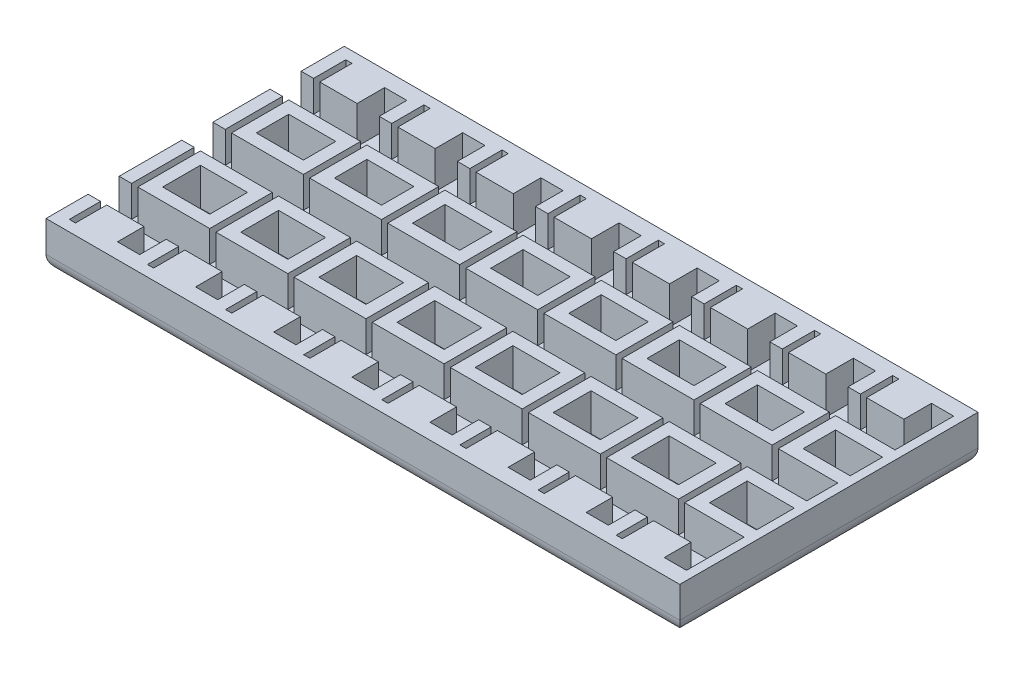
SolidWorks part; units mm, degrees
ref_plane "Alzado" through (0, 0, 0) normal (0, 0, 1) x (1, 0, 0)
ref_plane "Planta" through (0, 0, 0) normal (0, 1, 0) x (1, 0, 0)
ref_plane "Vista lateral" through (0, 0, 0) normal (1, 0, 0) x (0, 0, -1)
sketch "Sketch1" plane through (0, 0, 0) normal (0, 1, 0) x (1, 0, 0)
  line L1 (-102, -48) -> (102, -48)
  line L2 (-102, -48) -> (-102, 48)
  line L3 (-102, 48) -> (102, 48)
  line L4 (102, -48) -> (102, 48)
  line L5 (-102, -48) -> (102, 48) construction
  line L6 (-102, 48) -> (102, -48) construction
  point P0 (0, 0)
  dimension "D1" = 96
  dimension "D2" = 204
extrude "Boss-Extrude1" add sketch "Sketch1" along normal blind 15
sketch "Sketch2" plane through (0, 15, 0) normal (0, 1, 0) x (1, 0, 0)
  line L0 (-102, 48) -> (-102, -48) construction
  line L1 (-98, 44.5) -> (-96, 44.5)
  line L2 (-98, 44.5) -> (-98, -44.5)
  line L3 (-98, -44.5) -> (-96, -44.5)
  line L4 (-96, 44.5) -> (-96, -44.5)
  line L5 (-98, 44.5) -> (-96, -44.5) construction
  line L6 (-98, -44.5) -> (-96, 44.5) construction
  line L7 (-72.854, 44.5) -> (-72.854, -44.5)
  line L8 (-72.854, 44.5) -> (-70.854, 44.5)
  line L9 (-70.854, 44.5) -> (-70.854, -44.5)
  line L10 (-72.854, -44.5) -> (-70.854, -44.5)
  line L11 (-47.708, 44.5) -> (-47.708, -44.5)
  line L12 (-47.708, 44.5) -> (-45.708, 44.5)
  line L13 (-45.708, 44.5) -> (-45.708, -44.5)
  line L14 (-47.708, -44.5) -> (-45.708, -44.5)
  line L15 (-22.562, 44.5) -> (-22.562, -44.5)
  line L16 (-22.562, 44.5) -> (-20.562, 44.5)
  line L17 (-20.562, 44.5) -> (-20.562, -44.5)
  line L18 (-22.562, -44.5) -> (-20.562, -44.5)
  line L19 (2.584, 44.5) -> (2.584, -44.5)
  line L20 (2.584, 44.5) -> (4.584, 44.5)
  line L21 (4.584, 44.5) -> (4.584, -44.5)
  line L22 (2.584, -44.5) -> (4.584, -44.5)
  line L23 (27.73, 44.5) -> (27.73, -44.5)
  line L24 (27.73, 44.5) -> (29.73, 44.5)
  line L25 (29.73, 44.5) -> (29.73, -44.5)
  line L26 (27.73, -44.5) -> (29.73, -44.5)
  line L27 (52.876, 44.5) -> (52.876, -44.5)
  line L28 (52.876, 44.5) -> (54.876, 44.5)
  line L29 (54.876, 44.5) -> (54.876, -44.5)
  line L30 (52.876, -44.5) -> (54.876, -44.5)
  line L31 (78.022, 44.5) -> (78.022, -44.5)
  line L32 (78.022, 44.5) -> (80.022, 44.5)
  line L33 (80.022, 44.5) -> (80.022, -44.5)
  line L34 (78.022, -44.5) -> (80.022, -44.5)
  line L35 (-72.854, 0) -> (-70.854, 0)
  point P4 (-97, 0)
  point P39 (-71.854, 0)
  dimension "D1" = 2
  dimension "D2" = 89
  dimension "D3" = 4
  dimension "D5" = 25.146
  dimension "D4" = 8
extrude "Cut-Extrude1" cut sketch "Sketch2" against normal blind 10 contours L2 L3 L4 L1 | L9 L10 L7 L8 | L11 L14 L13 L12 | L15 L18 L17 L16 | L19 L22 L21 L20 | L23 L26 L25 L24 | L29 L30 L27 L28 | L31 L34 L33 L32
sketch "Sketch3" plane through (0, 15, 0) normal (0, 1, 0) x (1, 0, 0)
  line L0 (-96, 5.7) -> (-88, 5.7)
  line L1 (-96, 44.5) -> (-96, -44.5) construction
  line L2 (-88, 5.7) -> (-88, -4.3)
  line L3 (-88, -4.3) -> (-96, -4.3)
  line L4 (-96, -4.3) -> (-96, 5.7)
  line L5 (-96, 34.125) -> (-88, 34.125)
  line L6 (-88, 34.125) -> (-88, 24.125)
  line L7 (-88, 24.125) -> (-96, 24.125)
  line L8 (-96, 24.125) -> (-96, 34.125)
  line L9 (-96, -24.45) -> (-88, -24.45)
  line L10 (-88, -24.45) -> (-88, -34.45)
  line L11 (-88, -34.45) -> (-96, -34.45)
  line L12 (-96, -34.45) -> (-96, -24.45)
  line L13 (-96, 0.7) -> (-88, 0.7) construction
  line L14 (-88, 29.125) -> (-96, 29.125) construction
  line L15 (-88, -29.45) -> (-96, -29.45) construction
  line L16 (-98, 44.5) -> (-98, -44.5) construction
  line L17 (-96, -43.875) -> (-98, -43.875) construction
  line L18 (-96, -43.875) -> (-96, 43.875) construction
  line L19 (-96, 43.875) -> (-98, 43.875) construction
  line L20 (-98, -43.875) -> (-98, 43.875) construction
  line L21 (-96, -43.875) -> (-98, 43.875) construction
  line L22 (-96, 43.875) -> (-98, -43.875) construction
  line L23 (-70.854, 24.125) -> (-70.854, 34.125)
  line L24 (-70.854, 34.125) -> (-62.854, 34.125)
  line L25 (-62.854, 34.125) -> (-62.854, 24.125)
  line L26 (-62.854, 24.125) -> (-70.854, 24.125)
  line L27 (-70.854, -4.3) -> (-70.854, 5.7)
  line L28 (-70.854, 5.7) -> (-62.854, 5.7)
  line L29 (-62.854, 5.7) -> (-62.854, -4.3)
  line L30 (-62.854, -4.3) -> (-70.854, -4.3)
  line L31 (-70.854, -34.45) -> (-70.854, -24.45)
  line L32 (-70.854, -24.45) -> (-62.854, -24.45)
  line L33 (-62.854, -24.45) -> (-62.854, -34.45)
  line L34 (-62.854, -34.45) -> (-70.854, -34.45)
  line L35 (-45.708, 24.125) -> (-45.708, 34.125)
  line L36 (-45.708, 34.125) -> (-37.708, 34.125)
  line L37 (-37.708, 34.125) -> (-37.708, 24.125)
  line L38 (-37.708, 24.125) -> (-45.708, 24.125)
  line L39 (-45.708, -4.3) -> (-45.708, 5.7)
  line L40 (-45.708, 5.7) -> (-37.708, 5.7)
  line L41 (-37.708, 5.7) -> (-37.708, -4.3)
  line L42 (-37.708, -4.3) -> (-45.708, -4.3)
  line L43 (-45.708, -34.45) -> (-45.708, -24.45)
  line L44 (-45.708, -24.45) -> (-37.708, -24.45)
  line L45 (-37.708, -24.45) -> (-37.708, -34.45)
  line L46 (-37.708, -34.45) -> (-45.708, -34.45)
  line L47 (-20.562, 24.125) -> (-20.562, 34.125)
  line L48 (-20.562, 34.125) -> (-12.562, 34.125)
  line L49 (-12.562, 34.125) -> (-12.562, 24.125)
  line L50 (-12.562, 24.125) -> (-20.562, 24.125)
  line L51 (-20.562, -4.3) -> (-20.562, 5.7)
  line L52 (-20.562, 5.7) -> (-12.562, 5.7)
  line L53 (-12.562, 5.7) -> (-12.562, -4.3)
  line L54 (-12.562, -4.3) -> (-20.562, -4.3)
  line L55 (-20.562, -34.45) -> (-20.562, -24.45)
  line L56 (-20.562, -24.45) -> (-12.562, -24.45)
  line L57 (-12.562, -24.45) -> (-12.562, -34.45)
  line L58 (-12.562, -34.45) -> (-20.562, -34.45)
  line L59 (4.584, 24.125) -> (4.584, 34.125)
  line L60 (4.584, 34.125) -> (12.584, 34.125)
  line L61 (12.584, 34.125) -> (12.584, 24.125)
  line L62 (12.584, 24.125) -> (4.584, 24.125)
  line L63 (4.584, -4.3) -> (4.584, 5.7)
  line L64 (4.584, 5.7) -> (12.584, 5.7)
  line L65 (12.584, 5.7) -> (12.584, -4.3)
  line L66 (12.584, -4.3) -> (4.584, -4.3)
  line L67 (4.584, -34.45) -> (4.584, -24.45)
  line L68 (4.584, -24.45) -> (12.584, -24.45)
  line L69 (12.584, -24.45) -> (12.584, -34.45)
  line L70 (12.584, -34.45) -> (4.584, -34.45)
  line L71 (29.73, 24.125) -> (29.73, 34.125)
  line L72 (29.73, 34.125) -> (37.73, 34.125)
  line L73 (37.73, 34.125) -> (37.73, 24.125)
  line L74 (37.73, 24.125) -> (29.73, 24.125)
  line L75 (29.73, -4.3) -> (29.73, 5.7)
  line L76 (29.73, 5.7) -> (37.73, 5.7)
  line L77 (37.73, 5.7) -> (37.73, -4.3)
  line L78 (37.73, -4.3) -> (29.73, -4.3)
  line L79 (29.73, -34.45) -> (29.73, -24.45)
  line L80 (29.73, -24.45) -> (37.73, -24.45)
  line L81 (37.73, -24.45) -> (37.73, -34.45)
  line L82 (37.73, -34.45) -> (29.73, -34.45)
  line L83 (54.876, 24.125) -> (54.876, 34.125)
  line L84 (54.876, 34.125) -> (62.876, 34.125)
  line L85 (62.876, 34.125) -> (62.876, 24.125)
  line L86 (62.876, 24.125) -> (54.876, 24.125)
  line L87 (54.876, -4.3) -> (54.876, 5.7)
  line L88 (54.876, 5.7) -> (62.876, 5.7)
  line L89 (62.876, 5.7) -> (62.876, -4.3)
  line L90 (62.876, -4.3) -> (54.876, -4.3)
  line L91 (54.876, -34.45) -> (54.876, -24.45)
  line L92 (54.876, -24.45) -> (62.876, -24.45)
  line L93 (62.876, -24.45) -> (62.876, -34.45)
  line L94 (62.876, -34.45) -> (54.876, -34.45)
  line L95 (80.022, 24.125) -> (80.022, 34.125)
  line L96 (80.022, 34.125) -> (88.022, 34.125)
  line L97 (88.022, 34.125) -> (88.022, 24.125)
  line L98 (88.022, 24.125) -> (80.022, 24.125)
  line L99 (80.022, -4.3) -> (80.022, 5.7)
  line L100 (80.022, 5.7) -> (88.022, 5.7)
  line L101 (88.022, 5.7) -> (88.022, -4.3)
  line L102 (88.022, -4.3) -> (80.022, -4.3)
  line L103 (80.022, -34.45) -> (80.022, -24.45)
  line L104 (80.022, -24.45) -> (88.022, -24.45)
  line L105 (88.022, -24.45) -> (88.022, -34.45)
  line L106 (88.022, -34.45) -> (80.022, -34.45)
  line L107 (-70.854, 44.5) -> (-70.854, -44.5) construction
  point P22 (-97, 0)
  dimension "D1" = 10
  dimension "D2" = 8
  dimension "D3" = 87.75
  dimension "D4" = 14.75
  dimension "D5" = 28.425
  dimension "D6" = 30.15
  dimension "D7" = 8
extrude "Cut-Extrude2" cut sketch "Sketch3" against normal blind 12
fillet "Fillet1" radius 5 4 edges at (0, 0, -48) (-102, 0, 0) (0, 0, 48) (102, 0, 0)
sketch "Sketch5" plane through (0, 15, 0) normal (0, 1, 0) x (1, 0, 0)
  line L1 (-76.854, 20.125) -> (-92, 20.125)
  line L2 (-76.854, 20.125) -> (-76.854, 9.7)
  line L3 (-76.854, 9.7) -> (-92, 9.7)
  line L4 (-92, 20.125) -> (-92, 9.7)
  line L5 (-76.854, 20.125) -> (-92, 9.7) construction
  line L6 (-76.854, 9.7) -> (-92, 20.125) construction
  line L7 (-76.854, -8.3) -> (-92, -8.3)
  line L8 (-76.854, -8.3) -> (-76.854, -20.45)
  line L9 (-76.854, -20.45) -> (-92, -20.45)
  line L10 (-92, -8.3) -> (-92, -20.45)
  line L11 (-76.854, -8.3) -> (-92, -20.45) construction
  line L12 (-76.854, -20.45) -> (-92, -8.3) construction
  line L13 (-72.854, 44.5) -> (-72.854, -44.5) construction
  line L14 (-96, -4.3) -> (-96, -24.45) construction
  line L15 (-88, -24.45) -> (-96, -24.45) construction
  line L16 (-96, -4.3) -> (-88, -4.3) construction
  line L17 (-88, 5.7) -> (-96, 5.7) construction
  line L18 (-96, 24.125) -> (-96, 5.7) construction
  line L19 (-96, 24.125) -> (-88, 24.125) construction
  line L20 (-72.854, 44.5) -> (-72.854, -44.5) construction
  line L21 (-88, -4.3) -> (-88, 5.7) construction
  line L22 (-84, -4.3) -> (-76.854, -4.3)
  line L23 (-84, -4.3) -> (-84, 5.7)
  line L24 (-84, 5.7) -> (-76.854, 5.7)
  line L25 (-76.854, -4.3) -> (-76.854, 5.7)
  line L26 (-84, -4.3) -> (-76.854, 5.7) construction
  line L27 (-84, 5.7) -> (-76.854, -4.3) construction
  line L31 (-84, -4.3) -> (-84, 5.7) construction
  line L32 (-84, -4.3) -> (-76.854, -4.3) construction
  line L33 (-76.854, -4.3) -> (-76.854, 5.7) construction
  line L34 (-84, 5.7) -> (-76.854, 5.7) construction
  line L39 (-102, -48) -> (102, -48) construction
  line L40 (-84, 43) -> (-76.854, 43)
  line L41 (-84, 43) -> (-84, 24.125)
  line L42 (-84, 24.125) -> (-76.854, 24.125)
  line L43 (-76.854, 43) -> (-76.854, 24.125)
  line L44 (-84, 43) -> (-76.854, 24.125) construction
  line L45 (-84, 24.125) -> (-76.854, 43) construction
  line L46 (-84, -24.45) -> (-76.854, -24.45)
  line L47 (-84, -24.45) -> (-84, -43)
  line L48 (-84, -43) -> (-76.854, -43)
  line L49 (-76.854, -24.45) -> (-76.854, -43)
  line L50 (-84, -24.45) -> (-76.854, -43) construction
  line L51 (-84, -43) -> (-76.854, -24.45) construction
  line L52 (102, 48) -> (-102, 48) construction
  line L53 (-84, -111.973) -> (-84, -101.973) [skipped]
  line L54 (-84, -111.973) -> (-76.854, -111.973) [skipped]
  line L55 (-76.854, -111.973) -> (-76.854, -101.973) [skipped]
  line L56 (-84, -101.973) -> (-76.854, -101.973) [skipped]
  line L57 (-84, 103.373) -> (-84, 113.373) [skipped]
  line L58 (-76.854, 103.373) -> (-76.854, 113.373) [skipped]
  line L59 (-84, 113.373) -> (-76.854, 113.373) [skipped]
  line L60 (-84, 103.373) -> (-76.854, 103.373) [skipped]
  point P0 (-84.427, 14.9125)
  point P5 (-84.427, -14.375)
  point P28 (-80.427, 0.7)
  point P34 (-80.427, 33.5625)
  point P50 (-80.427, -33.725)
  point P57 (-80.427, -43)
  dimension "D1" = 4
  dimension "D2" = 4
  dimension "D3" = 4
  dimension "D4" = 4
  dimension "D5" = 4
  dimension "D6" = 4
  dimension "D7" = 4
  dimension "D8" = 4
  dimension "D9" = 4
  dimension "D10" = 4
  dimension "D11" = 4
  dimension "D12" = 4
  dimension "D15" = 5
  dimension "D16" = 5
  dimension "D17" = 4
  dimension "D13" = 2
  dimension "D14" = 2
extrude "Cut-Extrude3" cut sketch "Sketch5" against normal blind 12
pattern_linear "LPattern1" count 8 spacing 25.146 along (1, 0, 0) of "Cut-Extrude3"
hole_wizard "CSK for M4 Hex Socket Countersunk Cap Screw1" positions "Sketch7" profile "Sketch8" countersink size "M4" standard "ISO" end condition through all
sketch "Sketch7" plane through (0, 3, 0) normal (0, 1, 0) x (1, 0, 0)
  point P0 (-59.3602, 14.6655)
  point P2 (66.5766, -14.375)
  point P4 (66.349, 14.6655)
  point P6 (-59.3602, -14.375)
sketch "Sketch8" plane through (-59.3602, 3, -14.6655) normal (1, 0, 0) x (0, 0, 1)
  line L0 (0, 0) -> (0, 3)
  line L1 (0, 3) -> (2.25, 3)
  line L2 (2.25, 3) -> (2.25, 2.23)
  line L3 (2.25, 2.23) -> (4.48, 0)
  line L5 (4.48, 0) -> (0, 0)
  line L6 (-2.25, 2.23) -> (-4.48, 0) construction
  line L11 (0, -6.35) -> (0, 107.95) construction
  dimension "Thru Hole Dia." = 4.5
  dimension "Thru Hole Depth" = 3
  dimension "Near C'Sink Dia." = 8.96
  dimension "Near C'Sink Angle" = 90
sketch "Sketch9" plane through (0, 15, 0) normal (0, 1, 0) x (1, 0, 0)
  line L5 (-102, 48) -> (-102, -48) construction
  line L6 (99.168, 24.125) -> (-102, 24.125)
  line L11 (99.168, 24.125) -> (99.168, 34.125)
  line L12 (99.168, 34.125) -> (-102, 34.125)
  line L17 (-102, 24.125) -> (-102, 34.125)
  line L18 (99.168, 24.125) -> (-102, 34.125) construction
  line L19 (99.168, 34.125) -> (-102, 24.125) construction
  line L20 (-88, 34.125) -> (-96, 34.125) construction
  line L21 (-88, 5.7) -> (-96, 5.7) construction
  line L22 (99.168, -4.3) -> (-102, -4.3)
  line L23 (99.168, -4.3) -> (99.168, 5.7)
  line L24 (99.168, 5.7) -> (-102, 5.7)
  line L25 (-102, -4.3) -> (-102, 5.7)
  line L26 (99.168, -4.3) -> (-102, 5.7) construction
  line L27 (99.168, 5.7) -> (-102, -4.3) construction
  line L28 (99.168, -24.45) -> (-102, -24.45)
  line L29 (99.168, -24.45) -> (99.168, -34.45)
  line L30 (99.168, -34.45) -> (-102, -34.45)
  line L31 (-102, -24.45) -> (-102, -34.45)
  line L32 (99.168, -24.45) -> (-102, -34.45) construction
  line L33 (99.168, -34.45) -> (-102, -24.45) construction
  line L34 (-96, -34.45) -> (-88, -34.45) construction
  point P4 (-1.416, 29.125)
  point P19 (-1.416, 0.7)
  point P25 (-1.416, -29.45)
extrude "Cut-Extrude4" cut sketch "Sketch9" against normal up to surface (12 mm away) up to face at (-84.427, 3, 14.375)
